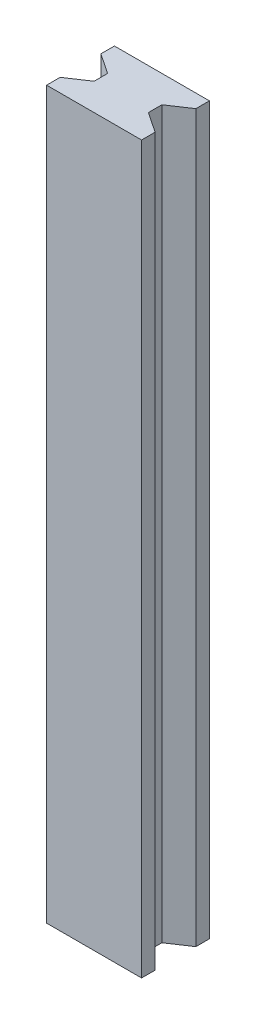
SolidWorks part; units mm, degrees
material "Aleación 1060"
ref_plane "Alzado" through (0, 0, 0) normal (0, 0, 1) x (1, 0, 0)
ref_plane "Planta" through (0, 0, 0) normal (0, 1, 0) x (1, 0, 0)
ref_plane "Vista lateral" through (0, 0, 0) normal (1, 0, 0) x (0, 0, -1)
sketch "Croquis2" plane through (0, 0, 0) normal (0, 1, 0) x (1, 0, 0)
  line L0 (-35, -15) -> (-20, -5)
  line L1 (-35, -25) -> (35, -25)
  line L2 (-35, -25) -> (-35, 25)
  line L3 (-35, 25) -> (35, 25)
  line L4 (35, -25) -> (35, 25)
  line L5 (-35, -25) -> (35, 25) construction
  line L6 (-35, 25) -> (35, -25) construction
  line L7 (-20, -5) -> (-20, 5)
  line L8 (-20, 5) -> (-35, 15)
  line L9 (20, -5) -> (35, -15)
  line L10 (20, 5) -> (20, -5)
  line L11 (35, 15) -> (20, 5)
  point P0 (0, 0)
  point P16 (0, 0)
  dimension "D1" = 70
  dimension "D2" = 50
  dimension "D3" = 15
  dimension "D4" = 10
  dimension "D5" = 10
  dimension "D6" = 20
  dimension "D7" = 20
  dimension "D8" = 2
extrude "Saliente-Extruir1" add sketch "Croquis2" along normal blind 535 contours L11 L4 L3 L2 L8 L7 L0 L1 L9 L10
